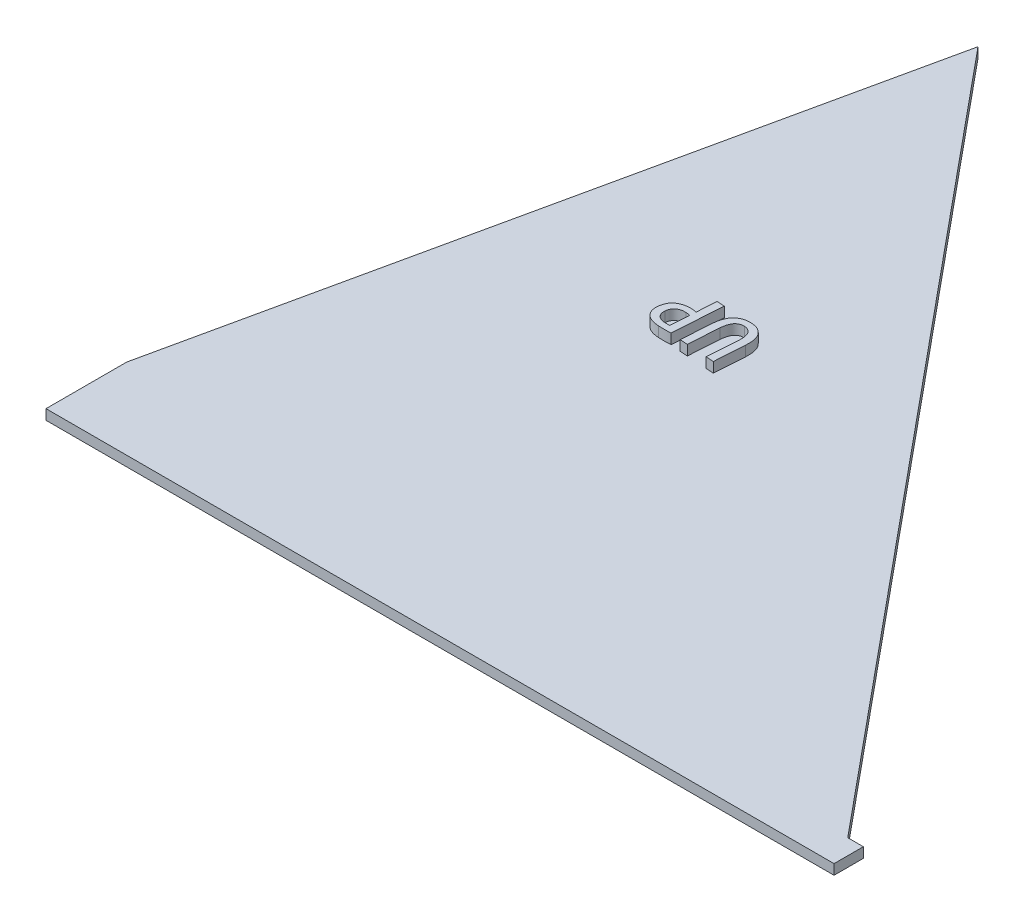
SolidWorks part; units mm, degrees
ref_plane "前视基准面" through (0, 0, 0) normal (0, 0, 1) x (1, 0, 0)
ref_plane "上视基准面" through (0, 0, 0) normal (0, 1, 0) x (1, 0, 0)
ref_plane "右视基准面" through (0, 0, 0) normal (1, 0, 0) x (0, 0, -1)
other "Configuration Table"
sketch "草图1" plane through (0, 0, 0) normal (0, 1, 0) x (1, 0, 0)
  line L0 (0, 0) -> (0, 9.9) construction
  line L1 (0, 9.9) -> (0.7827, 9.9) construction
  line L2 (0.7827, 9.9) -> (15.5031, 77.3262) construction
  line L3 (15.5031, 77.3262) -> (79.4026, 0) construction
  line L4 (79.4026, 0) -> (0, 0) construction
  line L5 (0, 0) -> (0, -5.17) construction
  line L6 (0, -5.17) -> (79.4026, -5.17) construction
  line L7 (79.4026, -5.17) -> (79.4026, 0) construction
  line L8 (2.7367, 9.4734) -> (16.5802, 72.8831)
  line L9 (16.5802, 72.8831) -> (77.8609, -1.274)
  line L10 (77.8609, -1.274) -> (79.4026, -1.274)
  line L11 (79.4026, -1.274) -> (79.4026, -4.17)
  line L12 (79.4026, -4.17) -> (1.5, -4.17)
  line L13 (1.5, -4.17) -> (1.5, 3.8088)
  line L14 (1.5, 3.8088) -> (2.7367, 9.4734)
  dimension "D1" = 9.9
  dimension "D2" = 0.7827
  dimension "D3" = 69.0144
  dimension "D4" = 79.4026
  dimension "D5" = 100.312
  dimension "D6" = 5.17
  dimension "D8" = 3
  dimension "D9" = 2
  dimension "D7" = 2
extrude "凸台-拉伸1" add sketch "草图1" along normal blind 1
sketch "草图2" plane through (0, 1, 0) normal (0, -1, 0) x (1, 0, 0)
  line L0 (9.0401, -38.3459) -> (47.2205, -35.8046) construction
  line L1 (16.5802, -72.8831) -> (1.5, -3.8088) construction
  line L2 (77.8609, 1.274) -> (16.5802, -72.8831) construction
  text T0 "UP" font "@Adobe 繁黑體 Std B" height 5
extrude "凸台-拉伸2" add sketch "草图2" against normal blind 1
